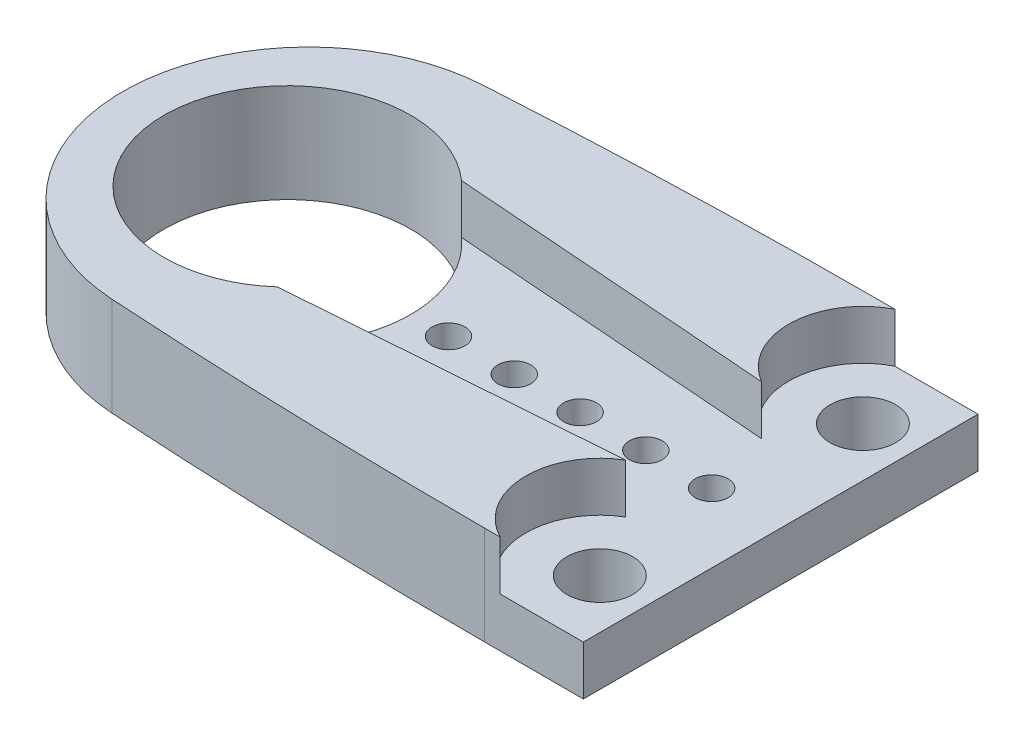
SolidWorks part; units mm, degrees
material "ABS"
ref_plane "Front Plane" through (0, 0, 0) normal (0, 0, 1) x (1, 0, 0)
ref_plane "Top Plane" through (0, 0, 0) normal (0, 1, 0) x (1, 0, 0)
ref_plane "Right Plane" through (0, 0, 0) normal (1, 0, 0) x (0, 0, -1)
sketch "Sketch1" plane through (0, 0, 0) normal (0, 1, 0) x (1, 0, 0)
  line L0 (0, 0) -> (11.2501, 0) construction
  line L1 (0.3, -5.6382) -> (0.3, 5.6382) construction
  line L12 (-5, 6) -> (15, 6)
  line L13 (-5, 6) -> (-5, -6)
  line L14 (-5, -6) -> (15, -6)
  line L15 (15, 6) -> (15, -6)
  line L16 (12, -6) -> (15, -6) construction
  line L17 (15, 6) -> (12, 6)
  line L18 (15, 6) -> (15, -6)
  line L19 (15, -6) -> (12, -6)
  line L20 (12, 6) -> (12, -6)
  line L21 (13.5, -6) -> (13.5, 6) construction
  circle A13 centre (0, 0) radius 2.35
  circle A14 centre (13.5, 4) radius 1
  circle A15 centre (13.5, -4) radius 1
  arc A16 (12, -6) -> (0.3, -5.6382) centre (12, 183.3717) cw
  arc A17 (12, 6) -> (0.3, 5.6382) centre (12, -183.3717) ccw
  arc A18 (0.3, 5.6382) -> (0.3, -5.6382) centre (0.649, 0) ccw
  dimension "D4" = 12
  dimension "D6" = 13.2
  dimension "D5" = 2
  dimension "D13" = 8
  dimension "D3" = 2
  dimension "D2" = 4.7
  dimension "D10" = 20
  dimension "D11" = 5
  dimension "D12" = 3
extrude "Boss-Extrude1" add sketch "Sketch1" against normal blind 3
sketch "Esquisse1" plane through (0, 0, 0) normal (0, 1, 0) x (1, 0, 0)
  line L2 (2.4945, -2.8) -> (14.1314, -1.9323)
  line L3 (14.1314, 1.9323) -> (2.4945, 2.8)
  line L4 (2.4945, -2.8) -> (14.1314, -1.9323)
  line L5 (14.1314, 1.9323) -> (2.4945, 2.8)
  arc A1 (2.4945, 2.8) -> (2.4945, -2.8) centre (0, 0) ccw
  arc A2 (2.4945, 2.8) -> (2.4945, -2.8) centre (0, 0) ccw
  spline S1 degree 2 poles (-5225.1953, 18257.7284) (-108.7077, -61.1491) (14.8275, -1.7461) (15.1573, -1.5874) (15.4072, -1.3186) (15.6562, -1.0506) (15.7906, -0.7092) (15.9249, -0.3678) (15.925, 0) (15.9251, 0.3662) (15.791, 0.708) (15.6574, 1.0487) (15.4078, 1.3179) (15.1591, 1.5861) (14.8286, 1.7455) (-108.3812, 61.1685) (-5366.9797, -18216.4275) knots -46.639454 -46.639454 -46.639454 0.125 0.125 0.25 0.25 0.375 0.375 0.5 0.5 0.625 0.625 0.75 0.75 0.875 0.875 47.521875 47.521875 47.521875 only from (14.1314, -1.9323) to (14.1314, 1.9323)
  spline S2 degree 2 poles (14.1314, -1.9323) (14.4973, -1.9048) (14.8275, -1.7461) (15.1573, -1.5874) (15.4072, -1.3186) (15.6562, -1.0506) (15.7906, -0.7092) (15.9249, -0.3678) (15.925, 0) (15.9251, 0.3662) (15.791, 0.708) (15.6574, 1.0487) (15.4078, 1.3179) (15.1591, 1.5861) (14.8286, 1.7455) (14.4984, 1.9047) (14.1314, 1.9323) knots 0 0 0 0.125 0.125 0.25 0.25 0.375 0.375 0.5 0.5 0.625 0.625 0.75 0.75 0.875 0.875 1 1 1
  dimension "D1" = 0
extrude "Enlèv. mat.-Extru.1" cut sketch "Esquisse1" against normal blind 1.5
sketch "Esquisse3" plane through (0, -1.5, 0) normal (0, 1, 0) x (1, 0, 0)
  circle A0 centre (4.9, 0) radius 0.5 construction
  circle A1 centre (6.9, 0) radius 0.5 construction
  circle A2 centre (8.9, 0) radius 0.5 construction
  circle A3 centre (10.9, 0) radius 0.5 construction
  circle A4 centre (12.9, 0) radius 0.5 construction
  circle A6 centre (4.9, 0) radius 0.5
  circle A7 centre (6.9, 0) radius 0.5
  circle A8 centre (8.9, 0) radius 0.5
  circle A9 centre (10.9, 0) radius 0.5
  circle A10 centre (12.9, 0) radius 0.5
  circle A11 centre (0, 0) radius 3.75
  arc A12 (2.4945, 2.8) -> (2.4945, -2.8) centre (0, 0) ccw construction
extrude "Enlèv. mat.-Extru.7" cut sketch "Esquisse3" against normal through all
ref_point "Point1"
sketch "Esquisse4" plane through (0, 0, 0) normal (0, 1, 0) x (1, 0, 0)
  line L0 (13.5, -1.75) -> (13.5, 1.75)
  line L1 (13.5, -6.25) -> (13.5, -9.0179)
  line L2 (13.5, -9.0179) -> (16.5752, -9.0179)
  line L3 (16.5752, -9.0179) -> (16.5752, 7.3522)
  line L4 (16.5752, 7.3522) -> (13.5, 7.3522)
  line L5 (13.5, 7.3522) -> (13.5, 6.25)
  arc A0 (13.5, -1.75) -> (13.5, -6.25) centre (13.5, -4) ccw
  arc A1 (13.5, 6.25) -> (13.5, 1.75) centre (13.5, 4) ccw
  circle A2 centre (13.5, 4) radius 1 construction
  circle A3 centre (13.5, -4) radius 1 construction
  dimension "D1" = 4.5
  dimension "D2" = 4.5
extrude "Enlèv. mat.-Extru.8" cut sketch "Esquisse4" against normal blind 1.5
